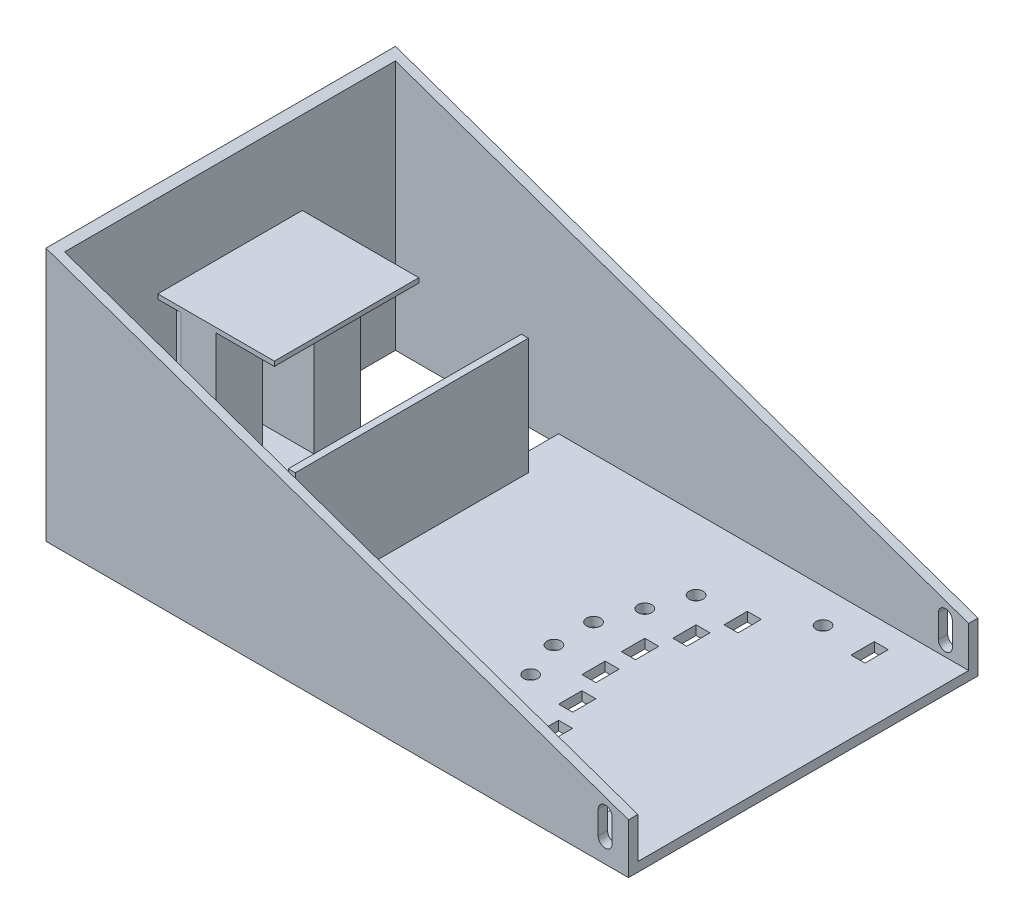
SolidWorks part; units mm, degrees
ref_plane "Front Plane" through (0, 0, 0) normal (0, 0, 1) x (1, 0, 0)
ref_plane "Top Plane" through (0, 0, 0) normal (0, 1, 0) x (1, 0, 0)
ref_plane "Right Plane" through (0, 0, 0) normal (1, 0, 0) x (0, 0, -1)
sketch "Sketch1" plane through (0, 0, 0) normal (0, 1, 0) x (1, 0, 0)
  line L0 (-196, 75) -> (-4, 75) construction
  line L1 (0, 0) -> (-200, 0)
  line L2 (0, 0) -> (0, 150)
  line L3 (0, 150) -> (-200, 150)
  line L4 (-200, 0) -> (-200, 150)
  line L5 (-196, 146) -> (-4, 146)
  line L6 (-196, 146) -> (-196, 4)
  line L7 (-196, 4) -> (-4, 4)
  line L8 (-4, 146) -> (-4, 4)
  line L9 (-196, 146) -> (-126, 146)
  line L10 (-196, 146) -> (-196, 106)
  line L11 (-196, 106) -> (-126, 106)
  line L12 (-126, 146) -> (-126, 106)
  line L13 (-196, 44) -> (-126, 44)
  line L14 (-126, 4) -> (-126, 44)
  line L15 (-196, 4) -> (-126, 4)
  line L16 (-196, 4) -> (-196, 44)
  line L17 (-171, 64) -> (-151, 64)
  line L18 (-171, 106) -> (-151, 106)
  line L19 (-171, 106) -> (-171, 86)
  line L20 (-171, 86) -> (-151, 86)
  line L21 (-151, 106) -> (-151, 86)
  line L22 (-151, 44) -> (-151, 64)
  line L23 (-171, 44) -> (-151, 44)
  line L24 (-171, 44) -> (-171, 64)
  line L25 (-163, 76) -> (-159, 76)
  line L26 (-163, 64) -> (-159, 64)
  line L27 (-163, 64) -> (-163, 74)
  line L28 (-163, 74) -> (-159, 74)
  line L29 (-159, 64) -> (-159, 74)
  line L30 (-159, 86) -> (-159, 76)
  line L31 (-163, 86) -> (-159, 86)
  line L32 (-163, 86) -> (-163, 76)
  dimension "D1" = 200
  dimension "D2" = 150
  dimension "D3" = 192
  dimension "D4" = 142
  dimension "D5" = 4
  dimension "D6" = 4
  dimension "D7" = 40
  dimension "D8" = 70
  dimension "D9" = 20
  dimension "D10" = 20
  dimension "D11" = 25
  dimension "D12" = 4
  dimension "D13" = 10
  dimension "D14" = 8
extrude "Boss-Extrude2" add sketch "Sketch1" along normal blind 4 contours L4 L1 L2 L3 L5 L8 L7 L6 | L0 L6 L13 L24 L17 L27 L28 L29 L22 L14 L7 L8 | L6 L0 L8 L5 L12 L11 L21 L20 L30 L25 L32 L19
sketch "Sketch2" plane through (0, 4, 0) normal (0, 1, 0) x (1, 0, 0)
  line L1 (-200, 0) -> (0, 0)
  line L2 (-200, 0) -> (-200, 150)
  line L3 (-200, 150) -> (0, 150)
  line L4 (0, 0) -> (0, 150)
  line L5 (-196, 146) -> (-4, 146)
  line L6 (-196, 146) -> (-196, 4)
  line L7 (-196, 4) -> (-4, 4)
  line L8 (-4, 146) -> (-4, 4)
  dimension "D1" = 4
  dimension "D2" = 4
extrude "Boss-Extrude3" add sketch "Sketch2" along normal blind 80
sketch "Sketch3" plane through (0, 0, 0) normal (0, 0, 1) x (1, 0, 0)
  line L0 (-200, 84) -> (0, 14)
  line L1 (0, 84) -> (0, 0) construction
  line L2 (0, 14) -> (0, 84)
  line L3 (0, 84) -> (-200, 84)
  dimension "D1" = 70
extrude "Cut-Extrude1" cut sketch "Sketch3" against normal blind 150
sketch "Sketch4" plane through (0, 4, 0) normal (0, 1, 0) x (1, 0, 0)
  line L6 (-4, 146) -> (-4, 4) construction
  line L17 (-4, 4) -> (-4, 146) construction
  line L18 (-13.5, 29.5) -> (-19.5, 29.5)
  line L19 (-13.5, 29.5) -> (-13.5, 39.5)
  line L20 (-13.5, 39.5) -> (-19.5, 39.5)
  line L21 (-19.5, 29.5) -> (-19.5, 39.5)
  line L22 (-196, 75) -> (-4, 75) construction
  line L23 (-196, 106) -> (-196, 44) construction
  line L24 (-13.5, 110.5) -> (-19.5, 110.5)
  line L25 (-19.5, 120.5) -> (-19.5, 110.5)
  line L26 (-13.5, 120.5) -> (-19.5, 120.5)
  line L27 (-13.5, 120.5) -> (-13.5, 110.5)
  line L28 (-19.5, 94.5) -> (-25.5, 94.5)
  line L29 (-19.5, 45.5) -> (-25.5, 45.5)
  line L30 (-19.5, 45.5) -> (-19.5, 55.5)
  line L31 (-19.5, 55.5) -> (-25.5, 55.5)
  line L32 (-25.5, 45.5) -> (-25.5, 55.5)
  line L33 (-25.5, 104.5) -> (-25.5, 94.5)
  line L34 (-19.5, 104.5) -> (-25.5, 104.5)
  line L35 (-19.5, 104.5) -> (-19.5, 94.5)
  line L36 (-25.5, 71.5) -> (-31.5, 71.5)
  line L37 (-25.5, 88.5) -> (-31.5, 88.5)
  line L38 (-25.5, 88.5) -> (-25.5, 78.5)
  line L39 (-25.5, 78.5) -> (-31.5, 78.5)
  line L40 (-31.5, 88.5) -> (-31.5, 78.5)
  line L41 (-31.5, 61.5) -> (-31.5, 71.5)
  line L42 (-25.5, 61.5) -> (-31.5, 61.5)
  line L43 (-25.5, 61.5) -> (-25.5, 71.5)
  circle A2 centre (-36.5, 115.5) radius 3
  circle A3 centre (-42.5, 99.5) radius 3
  circle A4 centre (-48.5, 83.5) radius 3
  circle A5 centre (-48.5, 66.5) radius 3
  circle A6 centre (-42.5, 50.5) radius 3
  circle A7 centre (-36.5, 34.5) radius 3
  dimension "D21" = 6
  dimension "D22" = 6
  dimension "D27" = 6
  dimension "D3" = 7
  dimension "D4" = 10
  dimension "D5" = 17
  dimension "D9" = 6
  dimension "D10" = 9.5
  dimension "D12" = 10
  dimension "D13" = 6
  dimension "D14" = 15.5
  dimension "D15" = 6
  dimension "D16" = 6
  dimension "D17" = 10
  dimension "D18" = 6
  dimension "D19" = 21.5
  dimension "D23" = 17
  dimension "D24" = 17
  dimension "D26" = 16
  dimension "D28" = 16
  dimension "D29" = 17
extrude "Cut-Extrude2" cut sketch "Sketch4" against normal blind 10
sketch "Sketch5" plane through (0, 0, 0) normal (1, 0, 0) x (0, 0, -1)
  line L0 (0, 0) -> (150, 0) construction
  line L1 (4, 15.4) -> (146, 15.4)
  line L2 (4, 15.4) -> (4, 4)
  line L3 (4, 4) -> (146, 4)
  line L4 (146, 15.4) -> (146, 4)
  line L6 (150, 14) -> (150, 0) construction
  dimension "D1" = 4
  dimension "D2" = 4
extrude "Cut-Extrude4" cut sketch "Sketch5" against normal blind 10
sketch "Sketch6" plane through (0, 4, 0) normal (0, 1, 0) x (1, 0, 0)
  line L0 (-196, 106) -> (-196, 44) construction
  line L1 (-171, 44) -> (-196, 44)
  line L2 (-171, 44) -> (-171, 64)
  line L3 (-171, 64) -> (-196, 64)
  line L4 (-196, 44) -> (-196, 64)
  line L6 (-171, 86) -> (-196, 86)
  line L7 (-171, 86) -> (-171, 106)
  line L8 (-171, 106) -> (-196, 106)
  line L9 (-196, 86) -> (-196, 106)
  dimension "D1" = 20
extrude "Boss-Extrude4" add sketch "Sketch6" along normal blind 66
sketch "Sketch7" plane through (0, 0, -106) normal (0, 0, -1) x (-1, 0, 0)
  line L0 (171, 70) -> (196, 70) construction
  line L1 (191, 70) -> (196, 70)
  line L2 (191, 70) -> (191, 32.5)
  line L3 (191, 32.5) -> (196, 32.5)
  line L4 (196, 70) -> (196, 32.5)
  dimension "D1" = 20
  dimension "D2" = 5
  dimension "D3" = 37.5
extrude "Cut-Extrude5" cut sketch "Sketch7" against normal blind 66
sketch "Sketch12" plane through (0, 0, 0) normal (0, 0, 1) x (1, 0, 0)
  line L0 (-200, 84) -> (-200, 109)
  line L1 (0, 14) -> (0, 39)
  line L2 (-200, 109) -> (0, 39)
  line L3 (-200, 84) -> (0, 14)
  dimension "D1" = 25
  dimension "D2" = 25
extrude "Boss-Extrude6" add sketch "Sketch12" against normal blind 4
sketch "Sketch13" plane through (0, 0, -150) normal (0, 0, -1) x (-1, 0, 0)
  line L0 (0, 14) -> (0, 39)
  line L1 (0, 39) -> (200, 109)
  line L2 (200, 109) -> (200, 84)
  line L3 (200, 84) -> (0, 14)
extrude "Boss-Extrude7" add sketch "Sketch13" against normal blind 4
sketch "Sketch14" plane through (0, 0, -146) normal (0, 0, 1) x (1, 0, 0)
  line L0 (-200, 84) -> (-200, 109)
  line L1 (-200, 84) -> (-196, 82.6)
  line L2 (-196, 82.6) -> (-196, 107.6)
  line L3 (-200, 109) -> (0, 39) construction
  line L4 (-196, 107.6) -> (-200, 109)
extrude "Boss-Extrude8" add sketch "Sketch14" along normal blind 142
fillet "Fillet1" radius 5 1 edges at (-191, 51.25, -106)
fillet "Fillet2" radius 5 1 edges at (-191, 51.25, -86)
fillet "Fillet3" radius 5 2 edges at (-191, 51.25, -44) (-191, 51.25, -64)
sketch "Sketch15" plane through (-196, 0, 0) normal (1, 0, 0) x (0, 0, -1)
  line L1 (44, 70) -> (106, 70)
  line L2 (44, 70) -> (44, 72)
  line L3 (44, 72) -> (106, 72)
  line L4 (106, 70) -> (106, 72)
  dimension "D1" = 62
  dimension "D2" = 2
extrude "Boss-Extrude9" add sketch "Sketch15" along normal blind 50
sketch "Sketch16" plane through (0, 4, 0) normal (0, 1, 0) x (1, 0, 0)
  line L0 (-151, 44) -> (-126, 44) construction
  line L1 (-151, 106) -> (-145, 106)
  line L2 (-151, 106) -> (-151, 86)
  line L3 (-151, 86) -> (-145, 86)
  line L4 (-145, 106) -> (-145, 86)
  line L5 (-151, 64) -> (-145, 64)
  line L6 (-151, 64) -> (-151, 44)
  line L7 (-151, 44) -> (-145, 44)
  line L8 (-145, 64) -> (-145, 44)
  dimension "D1" = 6
  dimension "D2" = 20
  dimension "D3" = 6
extrude "Cut-Extrude8" cut sketch "Sketch16" against normal blind 50
sketch "Sketch17" plane through (0, 4, 0) normal (0, 1, 0) x (1, 0, 0)
  line L0 (-159, 64) -> (-145, 64) construction
  line L1 (-164.5, 74) -> (-157.5, 74)
  line L2 (-164.5, 74) -> (-164.5, 64)
  line L3 (-164.5, 64) -> (-157.5, 64)
  line L4 (-157.5, 74) -> (-157.5, 64)
  line L7 (-171, 86) -> (-163, 86) construction
  line L8 (-164.5, 86) -> (-157.5, 86)
  line L9 (-164.5, 86) -> (-164.5, 76)
  line L10 (-164.5, 76) -> (-157.5, 76)
  line L11 (-157.5, 86) -> (-157.5, 76)
  dimension "D1" = 10
  dimension "D2" = 1.5
  dimension "D3" = 1.5
  dimension "D4" = 10
  dimension "D5" = 1.5
  dimension "D6" = 1.5
extrude "Cut-Extrude9" cut sketch "Sketch17" against normal blind 50
sketch "Sketch18" plane through (0, 0, 0) normal (0, -1, 0) x (1, 0, 0)
  line L1 (0, 0) -> (50, 0)
  line L2 (0, 0) -> (0, -150)
  line L3 (0, -150) -> (50, -150)
  line L4 (50, 0) -> (50, -150)
  dimension "D1" = 50
  dimension "D2" = 150
extrude "Boss-Extrude10" add sketch "Sketch18" against normal blind 4
sketch "Sketch19" plane through (0, 4, 0) normal (0, 1, 0) x (1, 0, 0)
  line L0 (0, 150) -> (50, 150)
  line L1 (0, 146) -> (50, 146)
  line L2 (50, 150) -> (50, 0) construction
  line L3 (50, 146) -> (50, 150)
  line L4 (0, 0) -> (50, 0)
  line L5 (0, 4) -> (50, 4)
  line L6 (50, 4) -> (50, 0)
  line L7 (0, 4) -> (0, 0)
  line L8 (0, 150) -> (0, 146)
extrude "Boss-Extrude11" add sketch "Sketch19" along normal blind 35
sketch "Sketch20" plane through (0, 0, 0) normal (0, 0, 1) x (1, 0, 0)
  line L5 (0, 39) -> (50, 21.5)
  line L6 (50, 39) -> (50, 0) construction
  line L7 (50, 21.5) -> (50, 39)
  line L8 (50, 39) -> (0, 39)
  dimension "D1" = 52.9741
extrude "Cut-Extrude10" cut sketch "Sketch20" against normal blind 210
sketch "Sketch21" plane through (0, 4, 0) normal (0, 1, 0) x (1, 0, 0)
  line L1 (19, 23.5) -> (25, 23.5)
  line L2 (19, 23.5) -> (19, 13.5)
  line L3 (19, 13.5) -> (25, 13.5)
  line L4 (25, 23.5) -> (25, 13.5)
  line L5 (-19.5, 29.5) -> (-13.5, 29.5) construction
  line L9 (50, 146) -> (50, 4) construction
  line L10 (50, 75) -> (-146, 75) construction
  line L11 (-146, 106) -> (-146, 44) construction
  line L12 (19, 136.5) -> (25, 136.5)
  line L13 (25, 126.5) -> (25, 136.5)
  line L14 (19, 126.5) -> (25, 126.5)
  line L15 (19, 126.5) -> (19, 136.5)
  line L17 (-196, 146) -> (50, 146) construction
  circle A0 centre (2, 131.5) radius 3
  circle A3 centre (2, 18.5) radius 3
  point P4 (25, 18.5)
  dimension "D5" = 6
  dimension "D6" = 14.5
  dimension "D7" = 17
  dimension "D1" = 6
  dimension "D2" = 6
  dimension "D3" = 10
  dimension "D4" = 25
extrude "Cut-Extrude11" cut sketch "Sketch21" against normal blind 30
sketch "Sketch22" plane through (0, 4, 0) normal (0, 1, 0) x (1, 0, 0)
  line L0 (-126, 4) -> (-126, 44) construction
  line L1 (-121, 25) -> (-118, 25)
  line L2 (-121, 25) -> (-121, 125)
  line L3 (-121, 125) -> (-118, 125)
  line L4 (-118, 25) -> (-118, 125)
  line L6 (-196, 146) -> (50, 146) construction
  dimension "D1" = 3
  dimension "D2" = 5
  dimension "D3" = 100
  dimension "D4" = 21
extrude "Boss-Extrude12" add sketch "Sketch22" along normal blind 50
sketch "Sketch23" plane through (0, 0, -150) normal (0, 0, -1) x (-1, 0, 0)
  line L0 (-40, 9) -> (-40, 19) construction
  line L1 (-43, 9) -> (-43, 19)
  line L2 (-37, 9) -> (-37, 19)
  line L3 (-50, 21.5) -> (-50, 0) construction
  line L4 (-50, 0) -> (200, 0) construction
  arc A0 (-43, 9) -> (-37, 9) centre (-40, 9) ccw
  arc A1 (-37, 19) -> (-43, 19) centre (-40, 19) ccw
  point P2 (-40, 14)
  dimension "D1" = 7
  dimension "D4" = 3
  dimension "D2" = 10
  dimension "D3" = 9
extrude "Cut-Extrude12" cut sketch "Sketch23" against normal blind 150
sketch "Sketch24" plane through (0, 0, -146) normal (0, 0, 1) x (1, 0, 0)
  line L0 (50, 4) -> (50, 25.7379)
  line L1 (50, 25.7379) -> (-199.9998, 113.2377)
  line L2 (-199.9998, 113.2377) -> (-199.9998, 109.2377)
  line L3 (-199.9998, 109.2377) -> (32, 27.8)
  line L4 (-196, 107.6) -> (50, 21.5) construction
  line L5 (32, 27.8) -> (32, 4)
  line L6 (50, 4) -> (-126, 4) construction
  line L7 (32, 4) -> (50, 4)
  dimension "D1" = 4
  dimension "D2" = 4
  dimension "D3" = 109.29
  dimension "D4" = 264.87
  dimension "D5" = 18
